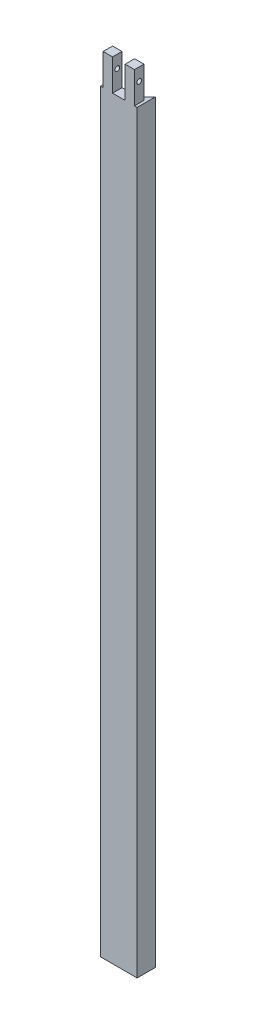
SolidWorks part; units mm, degrees
ref_plane "Front Plane" through (0, 0, 0) normal (0, 0, 1) x (1, 0, 0)
ref_plane "Top Plane" through (0, 0, 0) normal (0, 1, 0) x (1, 0, 0)
ref_plane "Right Plane" through (0, 0, 0) normal (1, 0, 0) x (0, 0, -1)
sketch "Sketch2" plane through (0, 0, 0) normal (0, 0, 1) x (1, 0, 0)
  line L1 (0, 0) -> (-6, 0)
  line L2 (0, 0) -> (0, -240)
  line L3 (0, -240) -> (-6, -240)
  line L4 (-6, 0) -> (-6, -240)
  dimension "D1" = 6
  dimension "D2" = 240
extrude "Boss-Extrude1" add sketch "Sketch2" along normal blind 3
sketch "Sketch4" plane through (0, -240, 0) normal (0, -1, 0) x (-1, 0, 0)
  line L0 (0, 0) -> (-2.8284, 2.8284)
  line L1 (-2.8284, 2.8284) -> (-2.8284, -3)
  line L2 (-2.8284, -3) -> (0, -3)
  line L3 (0, -3) -> (0, 0)
  line L4 (3, 0) -> (3, -3.7119) construction
  line L5 (6, 0) -> (0, 0) construction
  line L6 (8.8284, -3) -> (6, -3)
  line L7 (8.8284, 2.8284) -> (8.8284, -3)
  line L8 (6, 0) -> (8.8284, 2.8284)
  line L9 (6, -3) -> (6, 0)
  dimension "D1" = 135
  dimension "D2" = 4
extrude "Boss-Extrude2" add sketch "Sketch4" against normal up to vertex (240 mm away)
sketch "Sketch5" plane through (0, 0, 0) normal (0, 1, 0) x (1, 0, 0)
  line L0 (2.8284, -3) -> (-8.8284, -3) construction
  line L1 (-8, -3) -> (-5, -3)
  line L2 (-8, -3) -> (-8, 0)
  line L3 (-8, 0) -> (-5, 0)
  line L4 (-5, -3) -> (-5, 0)
  line L5 (-3, 0) -> (-3, -4.0355) construction
  line L6 (0, 0) -> (-6, 0) construction
  line L7 (2, 0) -> (-1, 0)
  line L8 (-1, -3) -> (-1, 0)
  line L9 (2, -3) -> (-1, -3)
  line L10 (2, -3) -> (2, 0)
  dimension "D1" = 3
  dimension "D2" = 2
  dimension "D3" = 0
extrude "Boss-Extrude3" add sketch "Sketch5" along normal blind 10
sketch "Sketch6" plane through (2, 0, 0) normal (1, 0, 0) x (0, 0, -1)
  line L0 (-3, 10) -> (-3, 0) construction
  line L1 (-3, 10) -> (0, 10) construction
  circle A0 centre (-1.5, 6) radius 0.75
  dimension "D1" = 1.5
  dimension "D2" = 1.5
  dimension "D3" = 4
extrude "Cut-Extrude1" cut sketch "Sketch6" against normal blind 40
